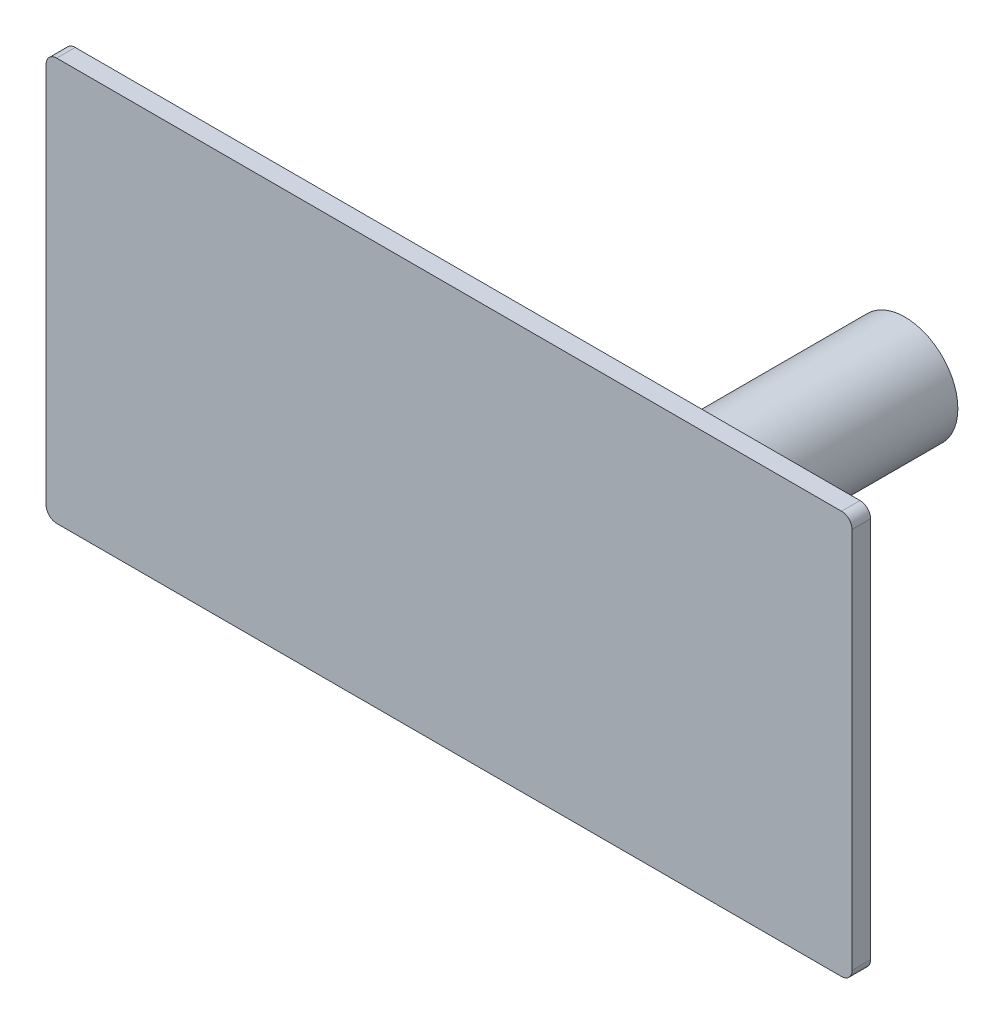
SolidWorks part; units mm, degrees
ref_plane "Front Plane" through (0, 0, 0) normal (0, 0, 1) x (1, 0, 0)
ref_plane "Top Plane" through (0, 0, 0) normal (0, 1, 0) x (1, 0, 0)
ref_plane "Right Plane" through (0, 0, 0) normal (1, 0, 0) x (0, 0, -1)
sketch "Sketch1" plane through (0, 0, 0) normal (0, 0, 1) x (1, 0, 0)
  line L1 (-38.1, -19.05) -> (38.1, -19.05)
  line L2 (-38.1, -19.05) -> (-38.1, 19.05)
  line L3 (-38.1, 19.05) -> (38.1, 19.05)
  line L4 (38.1, -19.05) -> (38.1, 19.05)
  line L5 (-38.1, -19.05) -> (38.1, 19.05) construction
  line L6 (-38.1, 19.05) -> (38.1, -19.05) construction
  point P0 (0, 0)
  dimension "D1" = 76.2
  dimension "D2" = 38.1
extrude "Boss-Extrude1" add sketch "Sketch1" along normal blind 1.75
fillet "Fillet1" radius 1 4 edges at (38.1, -19.05, 0.875) (-38.1, 19.05, 0.875) (38.1, 19.05, 0.875) (-38.1, -19.05, 0.875)
sketch "Sketch2" plane through (0, 0, 1.75) normal (0, 0, 1) x (1, 0, 0)
  line L0 (-37.1, -19.05) -> (37.1, -19.05) construction
  line L2 (38.1, -18.05) -> (38.1, 18.05) construction
  circle A0 centre (13.1, 2.95) radius 5
  dimension "D3" = 10
  dimension "D1" = 22
  dimension "D2" = 25
extrude "Boss-Extrude2" add sketch "Sketch2" against normal blind 30
sketch "Sketch4" plane through (0, 0, 1.75) normal (0, 0, 1) x (1, 0, 0)
  line L0 (-38.1, 18.05) -> (-38.1, -18.05) construction
  line L1 (-38.1, 3) -> (-33.1, 3)
  line L2 (-38.1, 3) -> (-38.1, 2)
  line L3 (-38.1, 2) -> (-33.1, 2)
  line L4 (-33.1, 3) -> (-33.1, 2)
  line L5 (-1000, 0) -> (49000, 0) construction
  line L6 (-38.1, -2) -> (-33.1, -2)
  line L7 (-33.1, -3) -> (-33.1, -2)
  line L8 (-38.1, -3) -> (-33.1, -3)
  line L9 (-38.1, -3) -> (-38.1, -2)
  line L10 (0, -1000) -> (0, 49000) construction
  line L11 (38.1, -3) -> (38.1, -2)
  line L12 (38.1, -3) -> (33.1, -3)
  line L13 (33.1, -3) -> (33.1, -2)
  line L14 (38.1, -2) -> (33.1, -2)
  line L15 (38.1, 2) -> (33.1, 2)
  line L16 (33.1, 3) -> (33.1, 2)
  line L17 (38.1, 3) -> (33.1, 3)
  line L18 (38.1, 3) -> (38.1, 2)
  line L19 (37.1, 19.05) -> (-37.1, 19.05) construction
  line L20 (-1, 19.05) -> (-2, 19.05)
  line L21 (-1, 19.05) -> (-1, 16.05)
  line L22 (-1, 16.05) -> (-2, 16.05)
  line L23 (-2, 19.05) -> (-2, 16.05)
  line L24 (1, 16.05) -> (2, 16.05)
  line L25 (2, 19.05) -> (2, 16.05)
  line L26 (1, 19.05) -> (2, 19.05)
  line L27 (1, 19.05) -> (1, 16.05)
  dimension "D1" = 1
  dimension "D2" = 5
  dimension "D3" = 2
  dimension "D4" = 1
  dimension "D5" = 3
  dimension "D6" = 2
extrude "Boss-Extrude3" [suppressed] add sketch "Sketch4" along normal blind 0.5 draft 30
